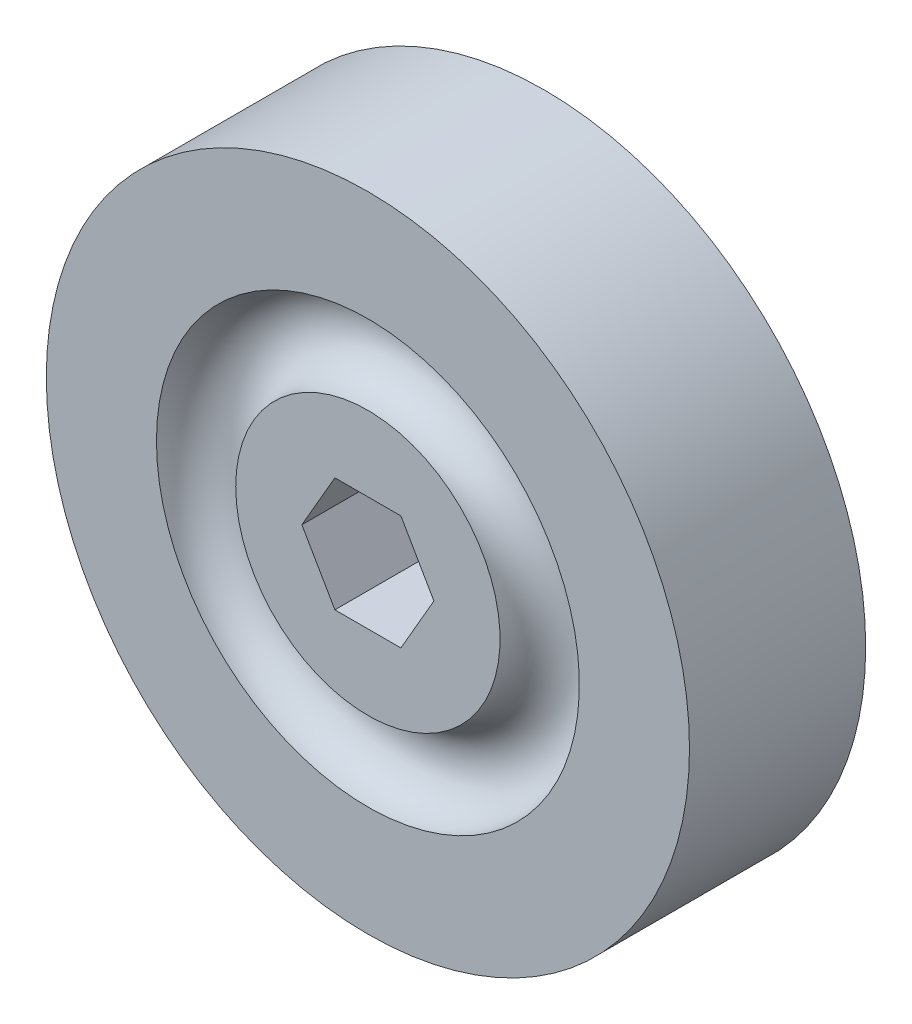
SolidWorks part; units mm, degrees
ref_plane "Front Plane" through (0, 0, 0) normal (0, 0, 1) x (1, 0, 0)
ref_plane "Top Plane" through (0, 0, 0) normal (0, 1, 0) x (1, 0, 0)
ref_plane "Right Plane" through (0, 0, 0) normal (1, 0, 0) x (0, 0, -1)
sketch "Sketch1" plane through (0, 0, 0) normal (0, 0, 1) x (1, 0, 0)
  line L1 (7.493, 0) -> (3.7465, 6.4891)
  line L2 (3.7465, 6.4891) -> (-3.7465, 6.4891)
  line L3 (-3.7465, 6.4891) -> (-7.493, 0)
  line L4 (-7.493, 0) -> (-3.7465, -6.4891)
  line L5 (-3.7465, -6.4891) -> (3.7465, -6.4891)
  line L6 (3.7465, -6.4891) -> (7.493, 0)
  circle A0 centre (0, 0) radius 6.4891 construction
  circle A1 centre (0, 0) radius 36.5
  circle A2 centre (0, 0) radius 15 construction
  circle A3 centre (0, 0) radius 24 construction
  dimension "D1" = 14.986
  dimension "D2" = 73
  dimension "D3" = 30
  dimension "D4" = 48
extrude "Boss-Extrude1" add sketch "Sketch1" along normal blind 20
sketch "Sketch2" plane through (0, 0, 0) normal (0, 1, 0) x (1, 0, 0)
  line L1 (-24, 0) -> (24, 0) construction
  line L3 (-24, 0) -> (-15, 0)
  arc A0 (-24, 0) -> (-15, 0) centre (-19.5, 0) ccw
sketch "Sketch3" plane through (0, 0, 0) normal (0, 0, -1) x (-1, 0, 0)
  circle A0 centre (0, 0) radius 19.5 construction
  circle A1 centre (0, 0) radius 19.5
sweep "Cut-Sweep2" cut profiles "Sketch2" path "Sketch3"
ref_plane "Plane1" through (0, 0, 10) normal (0, 0, 1) x (1, 0, 0)
mirror "Mirror1" about plane through (0, 0, 10) normal (0, 0, 1) of "Cut-Sweep2"
